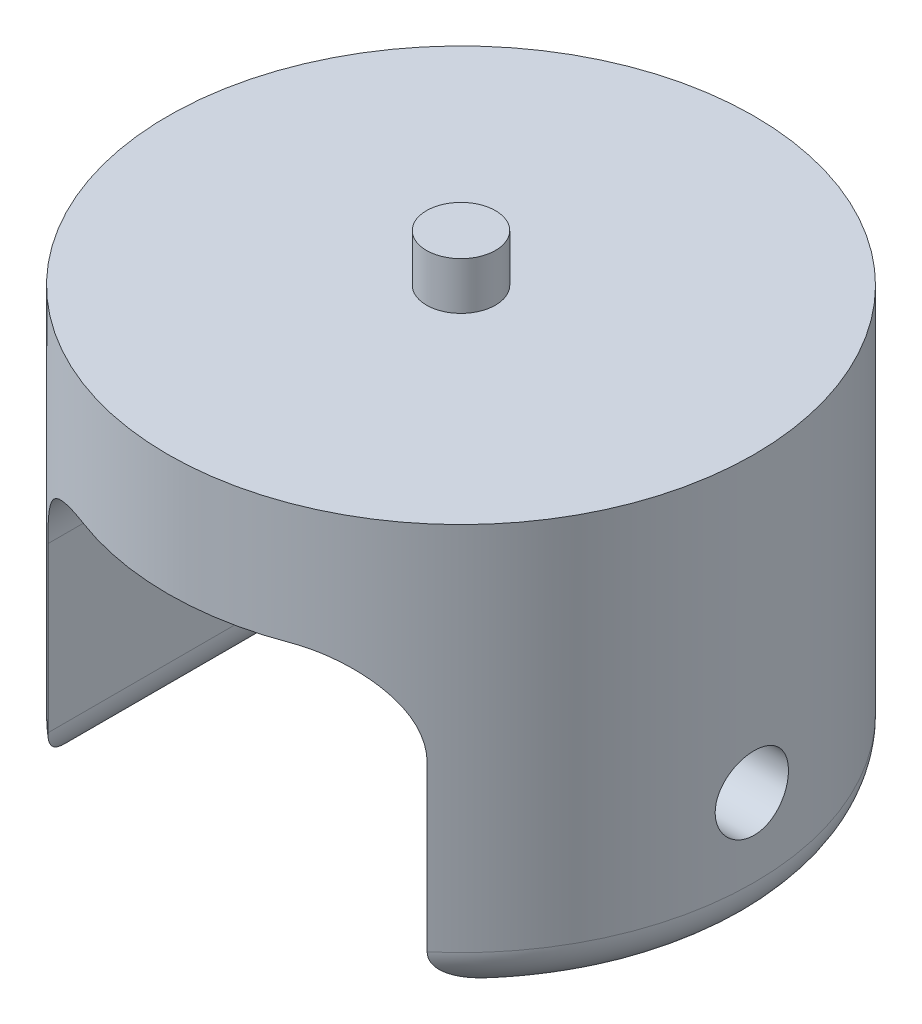
SolidWorks part; units mm, degrees
ref_plane "Front Plane" through (0, 0, 0) normal (0, 0, 1) x (1, 0, 0)
ref_plane "Top Plane" through (0, 0, 0) normal (0, 1, 0) x (1, 0, 0)
ref_plane "Right Plane" through (0, 0, 0) normal (1, 0, 0) x (0, 0, -1)
sketch "Sketch1" plane through (0, 0, 0) normal (0, 1, 0) x (1, 0, 0)
  circle A0 centre (0, 0) radius 34
extrude "Boss-Extrude1" add sketch "Sketch1" along normal blind 48
sketch "Sketch3" plane through (0, 0, 0) normal (0, 0, 1) x (1, 0, 0)
  line L0 (0, 0) -> (0, 34) construction
  line L1 (0, 34) -> (22, 34) construction
  line L2 (22, 34) -> (-22, 34) construction
  line L3 (22, 24) -> (22, 0)
  line L4 (-22, 24) -> (-22, 0)
  line L5 (12, 34) -> (-12, 34)
  line L6 (-34, 0) -> (34, 0) construction
  arc A0 (-22, 24) -> (-12, 34) centre (-12, 24) cw
  arc A1 (22, 24) -> (12, 34) centre (12, 24) ccw
  dimension "D3" = 10
  dimension "D1" = 22
  dimension "D2" = 22
  dimension "D4" = 34
extrude "Cut-Extrude1" cut sketch "Sketch3" against normal through all both and the other way through all
fillet "Fillet6" radius 5 4 edges at (22, 0, 0) (34, 0, 0) (-34, 0, 0) (-22, 0, 0)
sketch "Sketch5" plane through (-22, 0, 0) normal (1, 0, 0) x (0, 0, -1)
  line L0 (34, 48) -> (-34, 48) construction
  line L1 (-25.923, 24) -> (-25.923, 5) construction
  circle A0 centre (0, 14) radius 4.25
  dimension "D1" = 34
  dimension "D2" = 25.923
extrude "Cut-Extrude2" cut sketch "Sketch5" against normal through all and the other way through all
sketch "Sketch6" plane through (-22, 0, 0) normal (1, 0, 0) x (0, 0, -1)
  circle A0 centre (0, 14) radius 9.55
extrude "Cut-Extrude3" cut sketch "Sketch6" against normal blind 6.2
sketch "Sketch7" plane through (0, 48, 0) normal (0, 1, 0) x (1, 0, 0)
  circle A0 centre (0, 0) radius 4
extrude "Boss-Extrude2" add sketch "Sketch7" along normal blind 5.5
